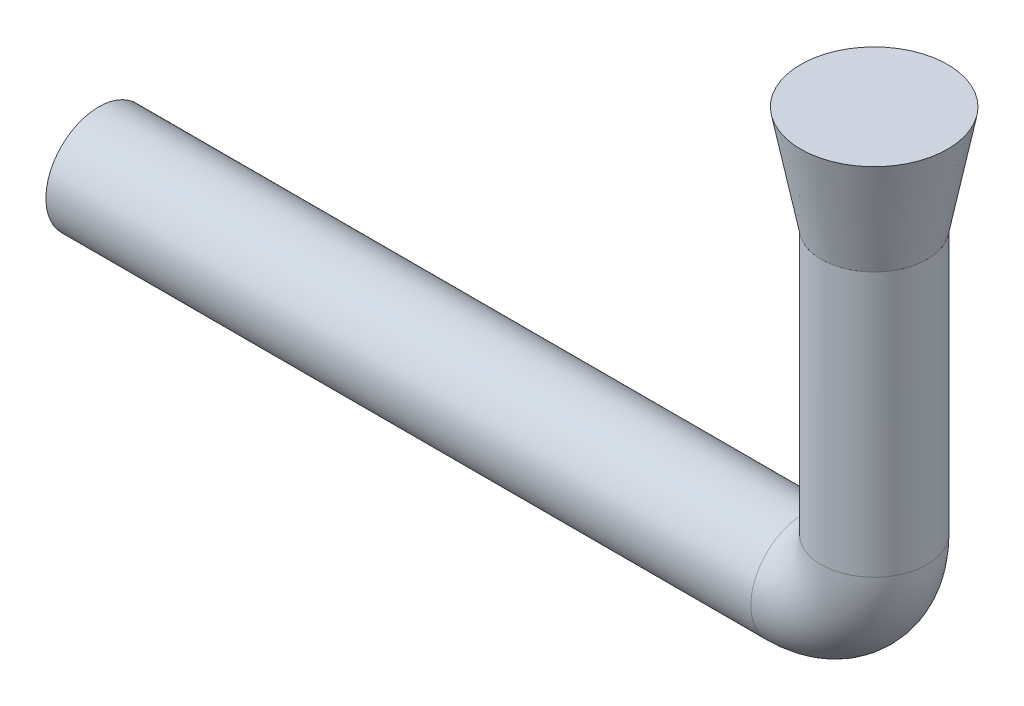
SolidWorks part; units mm, degrees
ref_plane "Front Plane" through (0, 0, 0) normal (0, 0, 1) x (1, 0, 0)
ref_plane "Top Plane" through (0, 0, 0) normal (0, 1, 0) x (1, 0, 0)
ref_plane "Right Plane" through (0, 0, 0) normal (1, 0, 0) x (0, 0, -1)
sketch "Sketch1" plane through (0, 0, 0) normal (0, 0, 1) x (1, 0, 0)
  line L0 (0, 0) -> (200, 0)
  line L1 (220, 20) -> (220, 95)
  arc A0 (200, 0) -> (220, 20) centre (200, 20) ccw
  dimension "D1" = 20
  dimension "D2" = 200
  dimension "D3" = 75
sweep "Sweep1" add path "Sketch1" circular profile diameter 30 parameters "D3"=30
sketch "Sketch30" plane through (0, 95, 0) normal (0, 1, 0) x (1, 0, 0)
  circle A1 centre (220, 0) radius 15
  circle A2 centre (220, 0) radius 15
  dimension "D1" = 0
extrude "Boss-Extrude1" add sketch "Sketch30" along normal blind 30 draft 11 separate body draft outward yes
